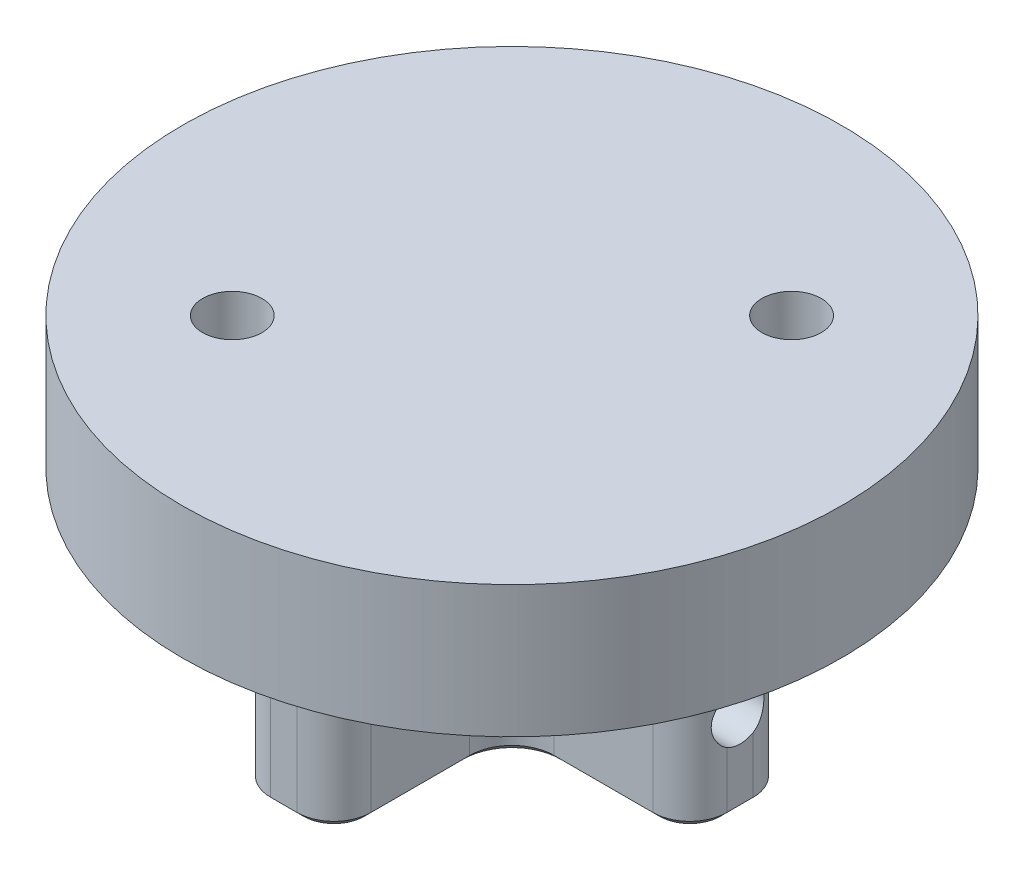
SolidWorks part; units mm, degrees
ref_plane "Front Plane" through (0, 0, 0) normal (0, 0, 1) x (1, 0, 0)
ref_plane "Top Plane" through (0, 0, 0) normal (0, 1, 0) x (1, 0, 0)
ref_plane "Right Plane" through (0, 0, 0) normal (1, 0, 0) x (0, 0, -1)
sketch "Sketch1" plane through (0, 0, 0) normal (0, 1, 0) x (1, 0, 0)
  circle A0 centre (0, 0) radius 25
  dimension "D1" = 50
extrude "Boss-Extrude1" add sketch "Sketch1" along normal blind 25
sketch "Sketch2" plane through (0, 0, 0) normal (0, -1, 0) x (1, 0, 0)
  line L24 (-17.3, 1) -> (-17.3, -1)
  line L25 (-7, 3.8) -> (-14.5, 3.8)
  line L26 (-3.8, 14.5) -> (-3.8, 7)
  line L27 (1, 17.3) -> (-1, 17.3)
  line L28 (3.8, 7) -> (3.8, 14.5)
  line L29 (14.5, 3.8) -> (7, 3.8)
  line L30 (17.3, -1) -> (17.3, 1)
  line L31 (7, -3.8) -> (14.5, -3.8)
  line L32 (3.8, -14.5) -> (3.8, -7)
  line L33 (-1, -17.3) -> (1, -17.3)
  line L34 (-3.8, -7) -> (-3.8, -14.5)
  line L35 (-14.5, -3.8) -> (-7, -3.8)
  line L36 (-17.3, 1) -> (-17.3, -1)
  line L37 (-7, 3.8) -> (-14.5, 3.8)
  line L38 (-3.8, 14.5) -> (-3.8, 7)
  line L39 (1, 17.3) -> (-1, 17.3)
  line L40 (3.8, 7) -> (3.8, 14.5)
  line L41 (14.5, 3.8) -> (7, 3.8)
  line L42 (17.3, -1) -> (17.3, 1)
  line L43 (7, -3.8) -> (14.5, -3.8)
  line L44 (3.8, -14.5) -> (3.8, -7)
  line L45 (-1, -17.3) -> (1, -17.3)
  line L46 (-3.8, -7) -> (-3.8, -14.5)
  line L47 (-14.5, -3.8) -> (-7, -3.8)
  arc A24 (-17.3, -1) -> (-14.5, -3.8) centre (-14.5, -1) ccw
  arc A25 (-14.5, 3.8) -> (-17.3, 1) centre (-14.5, 1) ccw
  arc A26 (-7, 3.8) -> (-3.8, 7) centre (-7, 7) ccw
  arc A27 (-1, 17.3) -> (-3.8, 14.5) centre (-1, 14.5) ccw
  arc A28 (3.8, 14.5) -> (1, 17.3) centre (1, 14.5) ccw
  arc A29 (3.8, 7) -> (7, 3.8) centre (7, 7) ccw
  arc A30 (17.3, 1) -> (14.5, 3.8) centre (14.5, 1) ccw
  arc A31 (14.5, -3.8) -> (17.3, -1) centre (14.5, -1) ccw
  arc A32 (7, -3.8) -> (3.8, -7) centre (7, -7) ccw
  arc A33 (1, -17.3) -> (3.8, -14.5) centre (1, -14.5) ccw
  arc A34 (-3.8, -14.5) -> (-1, -17.3) centre (-1, -14.5) ccw
  arc A35 (-3.8, -7) -> (-7, -3.8) centre (-7, -7) ccw
  arc A36 (-17.3, -1) -> (-14.5, -3.8) centre (-14.5, -1) ccw
  arc A37 (-14.5, 3.8) -> (-17.3, 1) centre (-14.5, 1) ccw
  arc A38 (-7, 3.8) -> (-3.8, 7) centre (-7, 7) ccw
  arc A39 (-1, 17.3) -> (-3.8, 14.5) centre (-1, 14.5) ccw
  arc A40 (3.8, 14.5) -> (1, 17.3) centre (1, 14.5) ccw
  arc A41 (3.8, 7) -> (7, 3.8) centre (7, 7) ccw
  arc A42 (17.3, 1) -> (14.5, 3.8) centre (14.5, 1) ccw
  arc A43 (14.5, -3.8) -> (17.3, -1) centre (14.5, -1) ccw
  arc A44 (7, -3.8) -> (3.8, -7) centre (7, -7) ccw
  arc A45 (1, -17.3) -> (3.8, -14.5) centre (1, -14.5) ccw
  arc A46 (-3.8, -14.5) -> (-1, -17.3) centre (-1, -14.5) ccw
  arc A47 (-3.8, -7) -> (-7, -3.8) centre (-7, -7) ccw
  dimension "D1" = 0.2
extrude "Boss-Extrude2" add sketch "Sketch2" along normal blind 14
sketch "Sketch3" plane through (-17.3, 0, 0) normal (-1, 0, 0) x (0, 0, 1)
  circle A0 centre (0, -7.5) radius 2 construction
  circle A1 centre (0, -7.5) radius 2
extrude "Cut-Extrude1" cut sketch "Sketch3" against normal through all
chamfer "Chamfer1" distance 0.5 angle 45 24 edges at (10.75, -14, 3.8) (4.7373, -14, 4.7373) (16.4799, -14, 2.9799) (3.8, -14, 10.75) (17.3, -14, 0) (2.9799, -14, 16.4799) (16.4799, -14, -2.9799) (0, -14, 17.3) (10.75, -14, -3.8) (-2.9799, -14, 16.4799) (4.7373, -14, -4.7373) (-3.8, -14, 10.75) (3.8, -14, -10.75) (-4.7373, -14, 4.7373) (2.9799, -14, -16.4799) (-10.75, -14, 3.8) (0, -14, -17.3) (-16.4799, -14, 2.9799) (-2.9799, -14, -16.4799) (-17.3, -14, 0) (-3.8, -14, -10.75) (-16.4799, -14, -2.9799) (-4.7373, -14, -4.7373) (-10.75, -14, -3.8)
sketch "Sketch7" plane through (0, 25, 0) normal (0, 1, 0) x (1, 0, 0)
  line L0 (-22.2122, -22.2122) -> (22.2122, 22.2122) construction
  line L1 (-25.3589, -19.0656) -> (19.0656, 25.3589)
  line L2 (-19.0656, -25.3589) -> (25.3589, 19.0656)
  line L3 (0, 0) -> (34.471, 0) construction
  arc A0 (-25.3589, -19.0656) -> (-19.0656, -25.3589) centre (-22.2122, -22.2122) ccw
  arc A1 (25.3589, 19.0656) -> (19.0656, 25.3589) centre (22.2122, 22.2122) ccw
  point P2 (0, 0)
  dimension "D1" = 45
  dimension "D2" = 8.9
extrude "Cut-Extrude3" cut sketch "Sketch7" against normal blind 15
hole_wizard "CBORE for M4 Hex Socket Head Cap Screw1" positions "Sketch5" profile "Sketch6" counterbore size "M4" standard "DIN"
sketch "Sketch5" plane through (0, 0, 0) normal (0, -1, 0) x (-1, 0, 0)
  line L2 (0, 0) -> (-10.6066, 10.6066) construction
  line L3 (0, 0) -> (0, 19.5798) construction
  line L4 (0, 0) -> (12.1342, 12.1342) construction
  point P0 (-10.6066, 10.6066)
  point P33 (10.6066, -10.6066)
  dimension "D1" = 45
  dimension "D2" = 30
sketch "Sketch6" plane through (10.6066, 0, -10.6066) normal (1, 0, 0) x (0, 0, -1)
  line L0 (0, 0) -> (0, 14.3519)
  line L1 (0, 14.3519) -> (2.25, 13)
  line L2 (2.25, 13) -> (2.25, 4.4)
  line L3 (2.25, 4.4) -> (4, 4.4)
  line L5 (4, 4.4) -> (4, 0.025)
  line L6 (4, 0.025) -> (4.025, 0)
  line L7 (4.025, 0) -> (0, 0)
  line L8 (-4, 0.025) -> (-4.025, 0) construction
  line L10 (0, 14.3519) -> (-2.25, 13) construction
  line L11 (0, -6.35) -> (0, 107.95) construction
  dimension "Hole Dia." = 4.5
  dimension "Hole Depth" = 13
  dimension "C'Bore Dia." = 8
  dimension "C'Bore Depth" = 4.4
  dimension "Near C'Sink Dia." = 8.05
  dimension "Near C'Sink Angle" = 90
  dimension "Drill Angle" = 118
sketch "Sketch8" plane through (0, 25, 0) normal (0, 1, 0) x (1, 0, 0)
  line L1 (20.542, 14.2487) -> (-14.2487, -20.542)
  line L2 (20.542, 14.2487) -> (-14.2487, -20.542)
  line L3 (-20.542, -14.2487) -> (14.2487, 20.542)
  line L4 (-20.542, -14.2487) -> (14.2487, 20.542)
  arc A1 (-14.2487, -20.542) -> (20.542, 14.2487) centre (0, 0) ccw
  arc A2 (-14.2487, -20.542) -> (20.542, 14.2487) centre (0, 0) ccw
  arc A3 (14.2487, 20.542) -> (-20.542, -14.2487) centre (0, 0) ccw
  arc A4 (14.2487, 20.542) -> (-20.542, -14.2487) centre (0, 0) ccw
  dimension "D1" = 0
  dimension "D2" = 0
extrude "Cut-Extrude4" cut sketch "Sketch8" against normal up to surface (15 mm away) up to face at (10.6066, 10, -8.3566)
